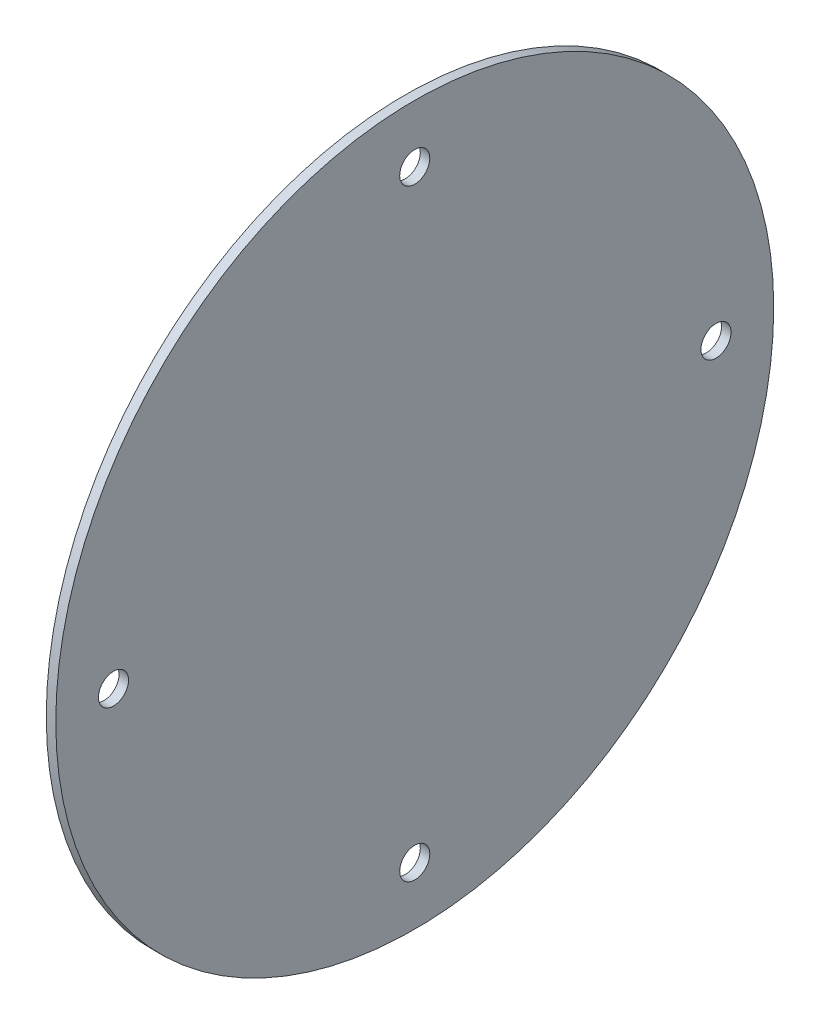
SolidWorks part; units mm, degrees
ref_plane "Front Plane" through (0, 0, 0) normal (1, 0, 0) x (0, 1, 0)
ref_plane "Top Plane" through (0, 0, 0) normal (0, 0, 1) x (0, 1, 0)
ref_plane "Right Plane" through (0, 0, 0) normal (0, 1, 0) x (-1, 0, 0)
sketch "Sketch1" plane through (0, 0, 0) normal (1, 0, 0) x (0, 1, 0)
  circle A0 centre (0, 0) radius 75.819
  dimension "D1" = 151.638
extrude "Boss-Extrude1" add sketch "Sketch1" along normal blind 2.0066
sketch "Sketch2" plane through (0, 0, 0) normal (-1, 0, 0) x (0, 0, 1)
  line L0 (75.819, 0) -> (63.627, 0)
  circle A0 centre (0, 0) radius 75.819 construction
  circle A1 centre (63.627, 0) radius 3.175
  dimension "D2" = 6.35
  dimension "D1" = 12.192
extrude "Cut-Extrude1" cut sketch "Sketch2" against normal through all contours A1
pattern_circular "CirPattern1" count 4 over 360 about axis through (0, 0, 0) along (1, 0, 0) of "Cut-Extrude1"
